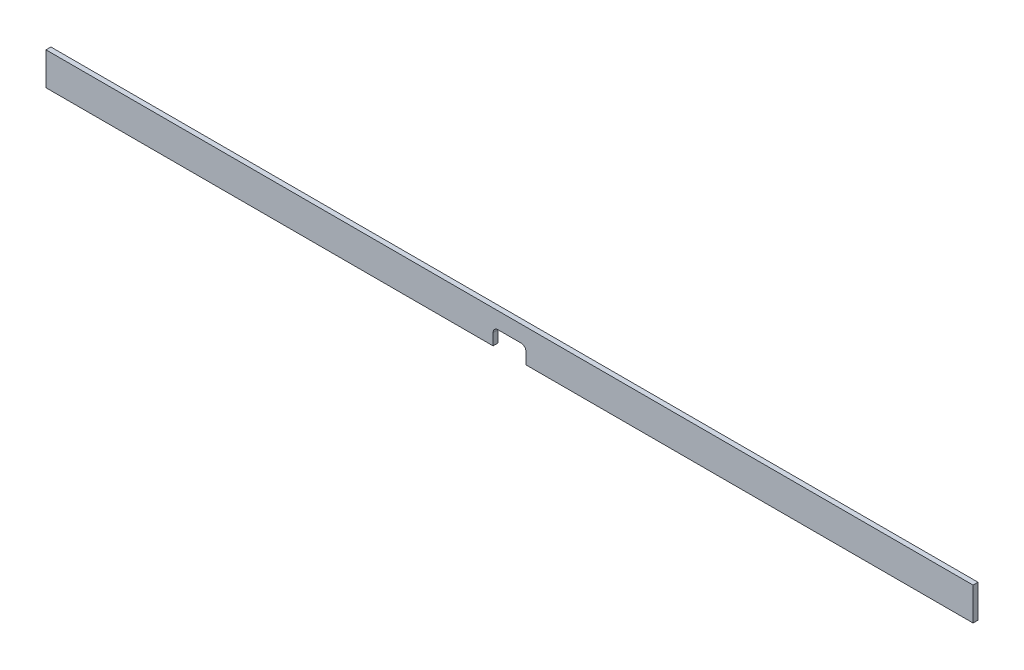
SolidWorks part; units mm, degrees
ref_plane "前基準面" through (0, 0, 0) normal (0, 0, 1) x (1, 0, 0)
ref_plane "上基準面" through (0, 0, 0) normal (0, 1, 0) x (1, 0, 0)
ref_plane "右基準面" through (0, 0, 0) normal (1, 0, 0) x (0, 0, -1)
sketch "草圖1" plane through (0, 0, 0) normal (0, 0, 1) x (1, 0, 0)
  line L0 (-10, -10) -> (10, -10)
  line L1 (-282, 10) -> (282, 10)
  line L2 (-282, 10) -> (-282, -10)
  line L3 (-282, -10) -> (282, -10)
  line L4 (282, 10) -> (282, -10)
  line L5 (-282, 10) -> (282, -10) construction
  line L6 (-282, -10) -> (282, 10) construction
  line L8 (-10, -10) -> (-10, -3)
  line L9 (-7, 0) -> (7, 0)
  line L10 (10, -10) -> (10, -3)
  line L13 (0, 0) -> (0, -10) construction
  arc A0 (7, 0) -> (10, -3) centre (7, -3) cw
  arc A1 (-10, -3) -> (-7, 0) centre (-7, -3) cw
  point P0 (0, 0)
  point P6 (0, -10)
  point P8 (0, 0)
  point P16 (10, 0)
  point P19 (-10, 0)
  dimension "D4" = 3
  dimension "D1" = 20
  dimension "D2" = 564
  dimension "D3" = 20
extrude "填料-伸長1" add sketch "草圖1" along normal blind 3 contours L8 A1 L9 A0 L10 L3 L4 L1 L2
